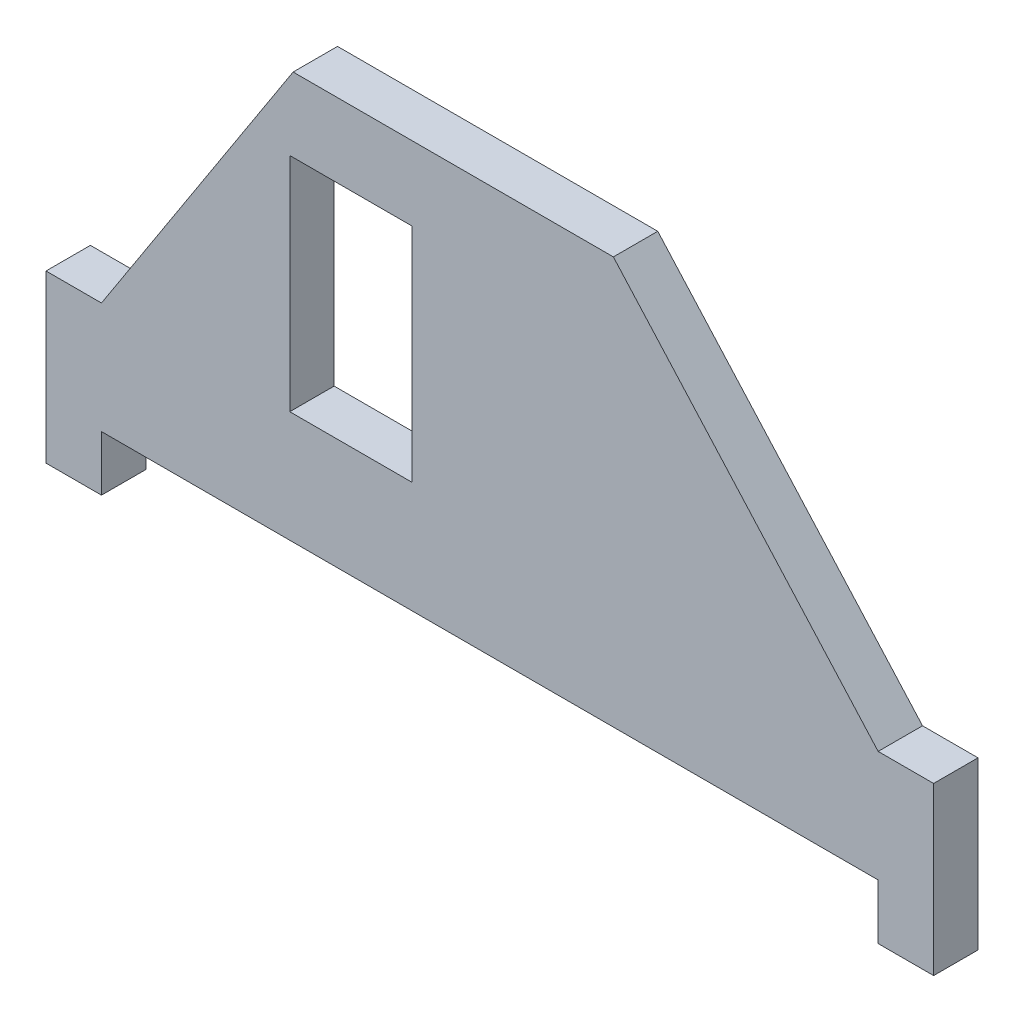
SolidWorks part; units mm, degrees
ref_plane "Front Plane" through (0, 0, 0) normal (0, 0, 1) x (1, 0, 0)
ref_plane "Top Plane" through (0, 0, 0) normal (0, 1, 0) x (1, 0, 0)
ref_plane "Right Plane" through (0, 0, 0) normal (1, 0, 0) x (0, 0, -1)
sketch "Sketch2" plane through (0, 0, 0) normal (0, 0, 1) x (1, 0, 0)
  line L0 (0, 381) -> (127, 381)
  line L1 (0, 0) -> (127, 0)
  line L2 (0, 0) -> (0, 381)
  line L3 (565.7515, 1058.3333) -> (1298.8708, 1058.3333)
  line L4 (2032, 0) -> (2032, 381)
  line L5 (127, 381) -> (565.7515, 1058.3333)
  line L6 (1298.8708, 1058.3333) -> (1905, 381)
  line L7 (127, 0) -> (127, 126.1335)
  line L8 (127, 126.1335) -> (1905, 126.1335)
  line L9 (1905, 0) -> (1905, 126.1335)
  line L10 (1905, 126.1335) -> (1905, 0)
  line L11 (558.038, 381) -> (837.438, 381)
  line L12 (558.038, 381) -> (837.438, 381)
  line L13 (558.038, 381) -> (558.038, 889)
  line L14 (558.038, 889) -> (837.438, 889)
  line L15 (837.438, 381) -> (837.438, 889)
  line L16 (1905, 381) -> (2032, 381)
  line L17 (1905, 0) -> (2032, 0)
  dimension "D1" = 2032
  dimension "D2" = 1067.562
  dimension "D3" = 381
  dimension "D4" = 127
  dimension "D5" = 127
  dimension "D6" = 127
  dimension "D7" = 127
  dimension "D8" = 508
  dimension "D9" = 279.4
extrude "Boss-Extrude2" add sketch "Sketch2" along normal blind 101.6 contours L9 L17 L4 L16 L6 L3 L5 L0 L2 L1 L7 L8 L15 L11 L13 L14
